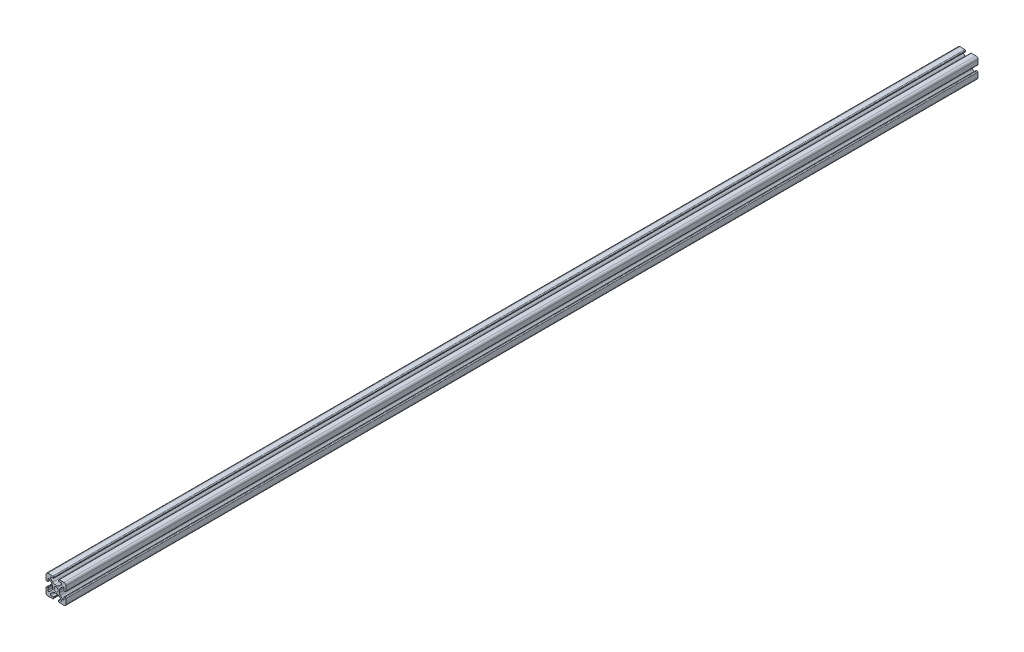
SolidWorks part; units mm, degrees
ref_plane "Front Plane" through (0, 0, 0) normal (0, 0, 1) x (1, 0, 0)
ref_plane "Top Plane" through (0, 0, 0) normal (0, 1, 0) x (1, 0, 0)
ref_plane "Right Plane" through (0, 0, 0) normal (1, 0, 0) x (0, 0, -1)
sketch "Sketch1" plane through (0, 0, 0) normal (0, 0, 1) x (1, 0, 0)
  line L0 (0, 0) -> (0, 10) construction
  line L1 (0, 0) -> (10, 0) construction
  line L2 (0, 0) -> (-10, 10) construction
  line L3 (-7.9302, 9.9988) -> (-3.2721, 9.8361)
  line L4 (-10, 10) -> (0, 10) construction
  line L6 (-2.8352, 8.0198) -> (-4.953, 8.0937)
  line L10 (0, 3.6) -> (-1.1022, 3.6)
  line L11 (-3.2236, 4.4787) -> (-5.5244, 6.7796)
  line L24 (0, 0) -> (-10, 0) construction
  line L25 (-10, 0) -> (0, 0) construction
  line L26 (0, 0) -> (0, -10) construction
  line L27 (-10, -10) -> (-10, 10) construction
  line L28 (0, 10) -> (10, 10) construction
  line L29 (-2.5249, 8.3091) -> (-2.5005, 9.0087)
  line L30 (-10, -10) -> (10, -10) construction
  arc A0 (-9.4142, 9.4142) -> (-7.9302, 9.9988) centre (-8, 8) cw
  arc A5 (-3.2721, 9.8361) -> (-2.5005, 9.0087) centre (-3.3, 9.0366) cw
  arc A6 (-1.1022, 3.6) -> (-3.2236, 4.4787) centre (-1.1022, 6.6) cw
  circle A16 centre (0, 0) radius 2.15
  arc A18 (-5.5244, 6.7796) -> (-4.953, 8.0937) centre (-4.9799, 7.3241) cw
  arc A20 (-2.8352, 8.0198) -> (-2.5249, 8.3091) centre (-2.8247, 8.3196) ccw
  point P15 (0, 0)
  point P42 (-2.3449, 3.6)
  point P80 (-10, 0)
  point P85 (0, -10)
  point P88 (0, -10)
  dimension "D11" = 2
  dimension "D15" = 3
  dimension "Center Hole Diameter" = 4.3
  dimension "D7" = 0.8
  dimension "D8" = 0.3
  dimension "D4" = 0.7701
  dimension "D1" = 45
  dimension "D2" = 2
  dimension "Rail Width" = 20
  dimension "T-Slot Depth" = 6.4
  dimension "D9" = 1.8
  dimension "Rail Height" = 20
  dimension "D23" = 7.2
  dimension "D5" = 11.5
  dimension "T-Slot Width" = 5
  dimension "D3" = 1.775
  dimension "D6" = 9.9598
sketch "Sketch2" plane through (0, 0, 0) normal (1, 0, 0) x (0, 0, -1)
  line L0 (-457.2, 0) -> (457.2, 0)
  line L1 (-457.2, -10) -> (-457.2, 10)
  line L2 (0, 0) -> (0, 10) construction
  line L3 (0, 0) -> (0, 10) construction
  line L4 (457.2, -10) -> (457.2, 10)
  point P0 (-427.2, 0)
  point P3 (0, 0)
  point P7 (427.2, 0)
  point P11 (-457.2, 0)
  point P14 (457.2, 0)
  dimension "D1" = 30
  dimension "Length" = 914.4
sketch "Sketch3" plane through (0, 0, 0) normal (0, 0, 1) x (1, 0, 0)
  line L0 (-2.5249, 8.3091) -> (-2.5005, 9.0087) construction
  line L1 (0, 0) -> (-10, 10) construction
  line L2 (0, 0) -> (-10, 10) construction
  line L5 (-7.9302, 9.9988) -> (-3.2721, 9.8361) construction
  line L6 (-2.8352, 8.0198) -> (-4.953, 8.0937) construction
  line L17 (-2.5249, 8.3091) -> (-2.5005, 9.0087)
  line L19 (-2.8352, 8.0198) -> (-4.953, 8.0937)
  line L20 (0, 0) -> (0, 10) construction
  line L21 (-3.6, 0) -> (-2.15, 0)
  line L22 (-3.6, 0) -> (-3.6, 1.1022)
  line L23 (-4.4787, 3.2236) -> (-6.7796, 5.5244)
  line L42 (-3.2236, 4.4787) -> (-5.5244, 6.7796) construction
  line L43 (0, 3.6) -> (-1.1022, 3.6) construction
  line L44 (-7.9302, 9.9988) -> (-3.2721, 9.8361)
  line L47 (-3.2236, 4.4787) -> (-5.5244, 6.7796)
  line L48 (0, 3.6) -> (-1.1022, 3.6)
  line L59 (0, 3.6) -> (0, 2.15)
  line L60 (-9.9988, 7.9302) -> (-9.8361, 3.2721)
  line L61 (-8.0198, 2.8352) -> (-8.0937, 4.953)
  line L62 (-8.3091, 2.5249) -> (-9.0087, 2.5005)
  arc A0 (-7.9302, 9.9988) -> (-9.4142, 9.4142) centre (-8, 8) ccw construction
  arc A1 (-2.8352, 8.0198) -> (-2.5249, 8.3091) centre (-2.8247, 8.3196) ccw construction
  arc A3 (-2.8352, 8.0198) -> (-2.5249, 8.3091) centre (-2.8247, 8.3196) ccw
  arc A5 (-7.9302, 9.9988) -> (-9.9988, 7.9302) centre (-8, 8) ccw
  circle A13 centre (0, 0) radius 2.15 construction
  arc A14 (0, 2.15) -> (-2.15, 0) centre (0, 0) ccw
  arc A15 (-4.4787, 3.2236) -> (-3.6, 1.1022) centre (-6.6, 1.1022) cw
  arc A16 (-8.0937, 4.953) -> (-6.7796, 5.5244) centre (-7.3241, 4.9799) cw
  arc A17 (-9.0087, 2.5005) -> (-9.8361, 3.2721) centre (-9.0366, 3.3) cw
  arc A18 (-8.0198, 2.8352) -> (-8.3091, 2.5249) centre (-8.3196, 2.8247) cw
  arc A36 (-2.5005, 9.0087) -> (-3.2721, 9.8361) centre (-3.3, 9.0366) ccw construction
  arc A38 (-4.953, 8.0937) -> (-5.5244, 6.7796) centre (-4.9799, 7.3241) ccw construction
  arc A39 (-3.2236, 4.4787) -> (-1.1022, 3.6) centre (-1.1022, 6.6) ccw construction
  arc A41 (-2.5005, 9.0087) -> (-3.2721, 9.8361) centre (-3.3, 9.0366) ccw
  arc A43 (-4.953, 8.0937) -> (-5.5244, 6.7796) centre (-4.9799, 7.3241) ccw
  arc A44 (-3.2236, 4.4787) -> (-1.1022, 3.6) centre (-1.1022, 6.6) ccw
extrude "Boss-Extrude1" add sketch "Sketch3" along normal mid plane 914.4
pattern_circular "CirPattern1" count 4 over 360 about axis through (0, 0, 0) along (0, 0, 1) of "Boss-Extrude1"
ref_plane "Contact Plane 1" through (0, 10, 0) normal (0, 1, 0) x (1, 0, 0)
ref_plane "Contact Plane 2" through (10, 0, 0) normal (1, 0, 0) x (0, 0, -1)
ref_plane "Contact Plane 3" through (0, -10, 0) normal (0, -1, 0) x (-1, 0, 0)
ref_plane "Contact Plane 4" through (-10, 0, 0) normal (-1, 0, 0) x (0, 0, 1)
equation "\"D1@Sketch2\"=\"Rail Width@Sketch1\"*1.5"
equation "\"D1@Boss-Extrude1\" = \"Length@Sketch2\""
